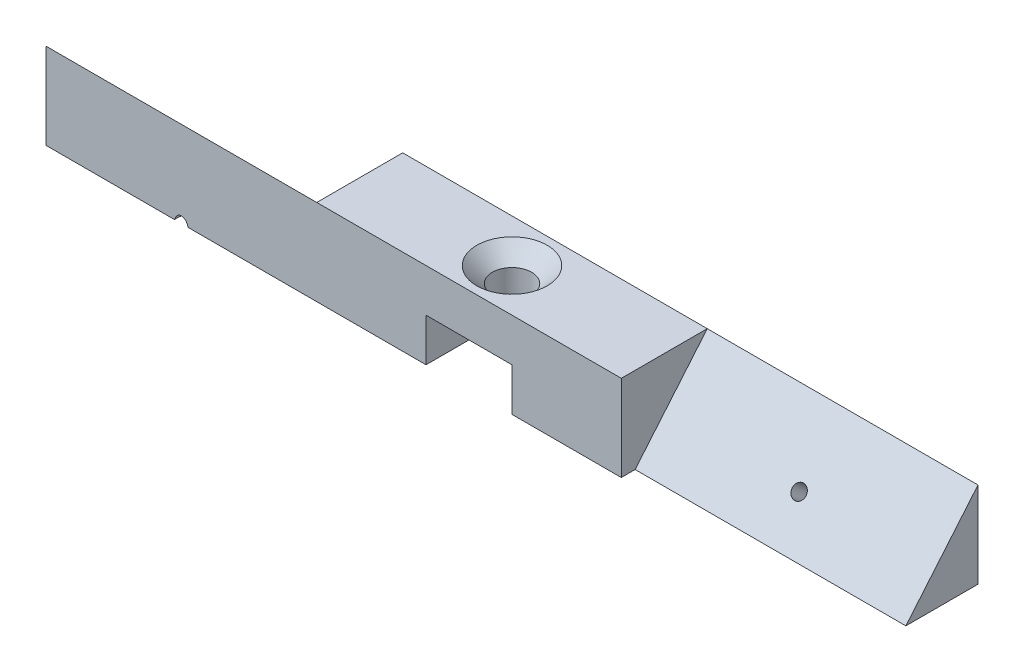
SolidWorks part; units mm, degrees
ref_plane "Front" through (0, 0, 0) normal (0, 0, 1) x (1, 0, 0)
ref_plane "Top" through (0, 0, 0) normal (0, 1, 0) x (1, 0, 0)
ref_plane "Right" through (0, 0, 0) normal (1, 0, 0) x (0, 0, -1)
sketch "Sketch1" plane through (0, 0, 0) normal (0, 1, 0) x (1, 0, 0)
  line L1 (-62.5, 6.35) -> (62.5, 6.35)
  line L2 (-62.5, 6.35) -> (-62.5, -6.35)
  line L3 (-62.5, -6.35) -> (62.5, -6.35)
  line L4 (62.5, 6.35) -> (62.5, -6.35)
  line L5 (-62.5, 6.35) -> (62.5, -6.35) construction
  line L6 (-62.5, -6.35) -> (62.5, 6.35) construction
  point P0 (0, 0)
  dimension "D1" = 12.7
  dimension "D2" = 125
extrude "Boss-Extrude1" add sketch "Sketch1" along normal blind 12.7
sketch "Sketch2" plane through (0, 0, 0) normal (0, -1, 0) x (1, 0, 0)
  line L0 (-62.5, 6.35) -> (62.5, 6.35) construction
  line L1 (-6.35, -6.35) -> (6.35, -6.35)
  line L2 (-6.35, -6.35) -> (-6.35, 6.35)
  line L3 (-6.35, 6.35) -> (6.35, 6.35)
  line L4 (6.35, -6.35) -> (6.35, 6.35)
  line L5 (-6.35, -6.35) -> (6.35, 6.35) construction
  line L6 (-6.35, 6.35) -> (6.35, -6.35) construction
  point P0 (0, 0)
  dimension "D1" = 12.7
extrude "Cut-Extrude1" cut sketch "Sketch2" against normal blind 6.35
sketch "Sketch4" plane through (0, 12.7, 0) normal (0, 1, 0) x (1, 0, 0)
  line L0 (0, 6.35) -> (0, 0) construction
  line L1 (62.5, 6.35) -> (-62.5, 6.35) construction
hole_wizard "CSK for M5 Flat Head Machine Screw1" positions "3DSketch2" profile "Sketch6" countersink size "M5" standard "ANSI Metric" end condition up to next
sketch3d "3DSketch2"
  point P0 (0, 12.7, 0)
sketch "Sketch6" plane through (0, 12.7, 0) normal (1, 0, 0) x (0, 0, 1)
  line L0 (0, 0) -> (0, 6.35)
  line L1 (0, 6.35) -> (2.9, 6.35)
  line L2 (2.9, 6.35) -> (2.9, 2.3)
  line L3 (2.9, 2.3) -> (5.2, 0)
  line L5 (5.2, 0) -> (0, 0)
  line L6 (-2.9, 2.3) -> (-5.2, 0) construction
  line L11 (0, -6.35) -> (0, 107.95) construction
  dimension "Thru Hole Dia." = 5.8
  dimension "Thru Hole Depth" = 6.35
  dimension "Near C'Sink Dia." = 10.4
  dimension "Near C'Sink Angle" = 90
sketch "Sketch7" plane through (62.5, 0, 0) normal (1, 0, 0) x (0, 0, -1)
  line L0 (6.35, 12.7) -> (-6.35, -2.4353)
  line L1 (-6.35, 12.7) -> (-6.35, 0) construction
  line L2 (-6.35, -2.4353) -> (-6.35, 12.7)
  line L3 (-6.35, 12.7) -> (6.35, 12.7)
  dimension "D1" = 50
extrude "Cut-Extrude2" cut sketch "Sketch7" against normal blind 40
sketch "Sketch8" plane through (0, 2.1206, 2.5272) normal (0, 0.6428, 0.766) x (1, 0, 0)
  line L0 (42.5, 13.8105) -> (42.5, 3.8105) construction
  line L1 (62.5, 13.8105) -> (22.5, 13.8105) construction
  dimension "D1" = 10
hole_wizard "Tap Drill for M2.5x0.45 Tap1" positions "3DSketch3" profile "Sketch9" hole size "M2.5x0.45" standard "ANSI Metric" end condition up to next
sketch3d "3DSketch3"
  point P0 (42.5, 5.0396, 0.0779)
sketch "Sketch9" plane through (42.5, 5.0396, 0.0779) normal (1, 0, 0) x (0, -0.766, 0.6428)
  line L0 (0, 0) -> (0, 8.1648)
  line L1 (0, 8.1648) -> (1.025, 8.1648)
  line L2 (1.025, 8.1648) -> (1.025, 0)
  line L5 (1.025, 0) -> (0, 0)
  line L11 (0, -6.35) -> (0, 107.95) construction
  dimension "Thru Hole Dia." = 2.05
  dimension "Thru Hole Depth" = 8.1648
pattern_circular "CirPattern1" count 2 over 360 about axis through (0, 0, 0) along (0, 1, 0) of "Cut-Extrude2", "Tap Drill for M2.5x0.45 Tap1"
